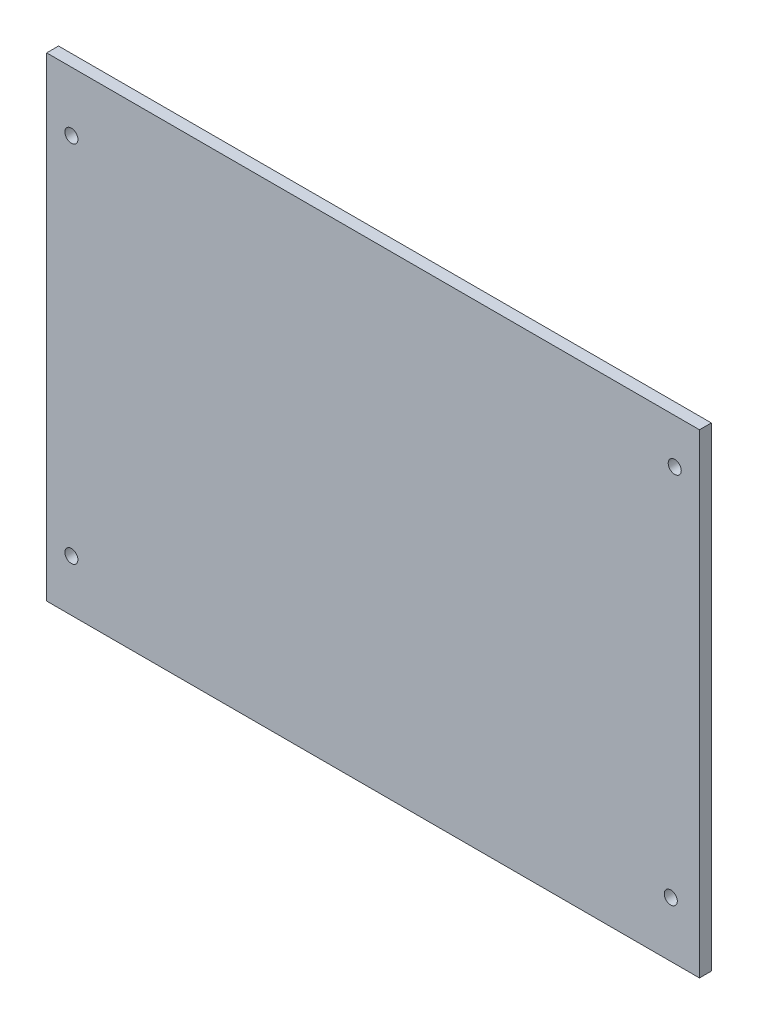
SolidWorks part; units mm, degrees
material "山毛榉"
ref_plane "前视基准面" through (0, 0, 0) normal (0, 0, 1) x (1, 0, 0)
ref_plane "上视基准面" through (0, 0, 0) normal (0, 1, 0) x (1, 0, 0)
ref_plane "右视基准面" through (0, 0, 0) normal (1, 0, 0) x (0, 0, -1)
sketch "草图1" plane through (0, 0, 0) normal (0, 0, 1) x (1, 0, 0)
  line L1 (0, 0) -> (330, 0)
  line L2 (0, 0) -> (0, -240)
  line L3 (0, -240) -> (330, -240)
  line L4 (330, 0) -> (330, -240)
  circle A4 centre (12.5, -30) radius 3.3
  circle A6 centre (315.4934, -212) radius 3.3
  circle A7 centre (12.5, -214) radius 3.3
  circle A8 centre (317.4934, -22.5) radius 3.3
  dimension "D5" = 6.6
  dimension "D10" = 184
  dimension "D12" = 6.6
  dimension "D13" = 6.6
  dimension "D14" = 6.6
  dimension "D1" = 330
  dimension "D6" = 189.5
  dimension "D11" = 303
  dimension "D15" = 7.5
  dimension "D16" = 30
  dimension "D17" = 12.5
  dimension "D18" = 2
extrude "凸台-拉伸1" add sketch "草图1" along normal blind 6
